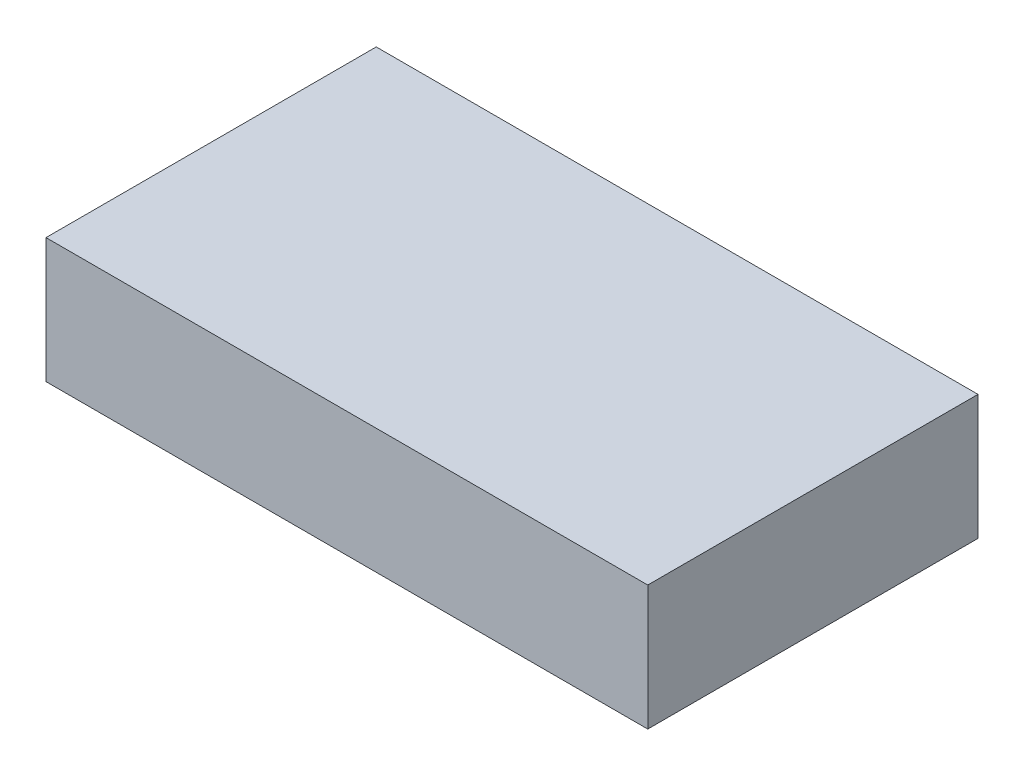
SolidWorks part; units mm, degrees
material "C1"
ref_plane "前基準面" through (0, 0, 0) normal (0, 0, 1) x (1, 0, 0)
ref_plane "上基準面" through (0, 0, 0) normal (0, 1, 0) x (1, 0, 0)
ref_plane "右基準面" through (0, 0, 0) normal (1, 0, 0) x (0, 0, -1)
sketch "草圖1" plane through (0, 0, 0) normal (0, 1, 0) x (1, 0, 0)
  line L1 (0, 0) -> (82, 0)
  line L2 (0, 0) -> (0, 45)
  line L3 (0, 45) -> (82, 45)
  line L4 (82, 0) -> (82, 45)
  dimension "D1" = 45
  dimension "D2" = 82
extrude "填料-伸長1" add sketch "草圖1" along normal blind 17
